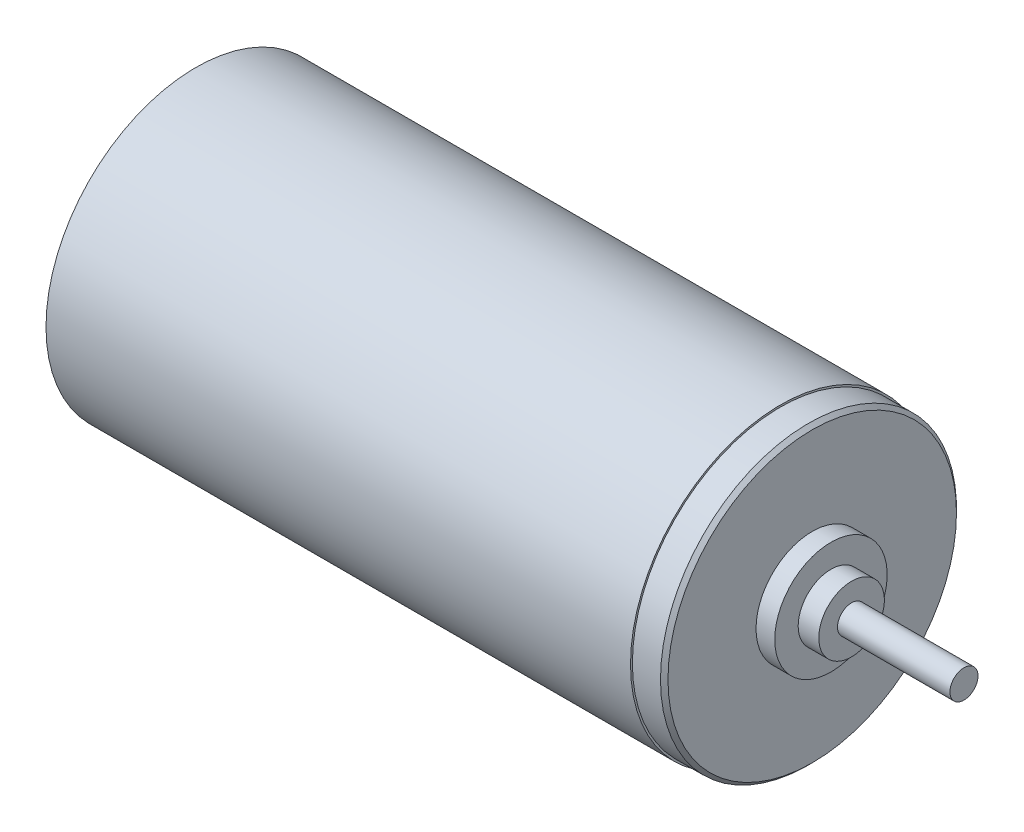
SolidWorks part; units mm, degrees
ref_plane "Plan de face" through (0, 0, 0) normal (0, 0, 1) x (1, 0, 0)
ref_plane "Plan de dessus" through (0, 0, 0) normal (0, 1, 0) x (1, 0, 0)
ref_plane "Plan de droite" through (0, 0, 0) normal (1, 0, 0) x (0, 0, -1)
sketch "Esquisse1" plane through (0, 0, 0) normal (0, 0, 1) x (1, 0, 0)
  line L0 (-60.2613, 0) -> (67.1346, 0) construction
  line L1 (-53.0314, 0) -> (-53.0314, 8)
  line L2 (-53.0314, 8) -> (-21.8314, 8)
  line L3 (-21.8314, 8) -> (-21.8314, 7.9)
  line L4 (-21.8314, 7.9) -> (-20.1314, 7.9)
  line L5 (-20.1314, 7.9) -> (-20.1314, 3)
  line L6 (-20.1314, 3) -> (-19.1314, 3)
  line L7 (-19.1314, 3) -> (-19.1314, 1.75)
  line L8 (-19.1314, 1.75) -> (-18.0314, 1.75)
  line L9 (-18.0314, 1.75) -> (-18.0314, 0.75)
  line L10 (-18.0314, 0.75) -> (-12.0314, 0.75)
  line L11 (-12.0314, 0.75) -> (-12.0314, 0)
  line L12 (-53.0314, 0) -> (-12.0314, 0)
  dimension "D1" = 8
  dimension "D2" = 31.2
  dimension "D3" = 0.1
  dimension "D4" = 1.7
  dimension "D5" = 3
  dimension "D6" = 1
  dimension "D7" = 1.1
  dimension "D8" = 3.5
  dimension "D9" = 6
  dimension "D10" = 0.75
revolve "Révolution1" add sketch "Esquisse1" angle 360 about L0
chamfer "Chanfrein1" distance 0.2 angle 45 1 edges at (-20.1314, 0, 7.9)
